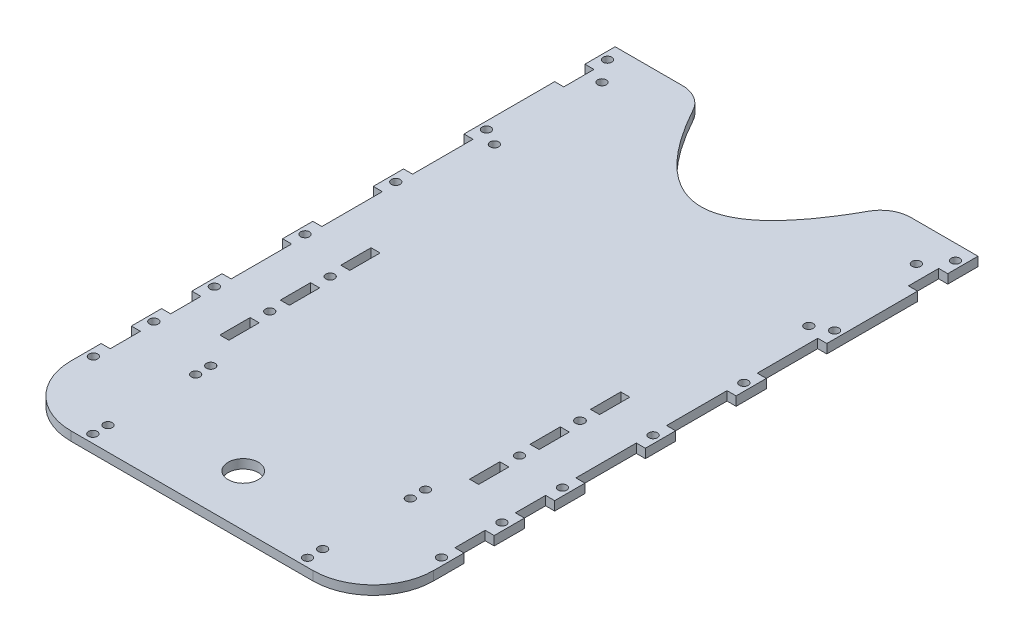
SolidWorks part; units mm, degrees
ref_plane "Front Plane" through (0, 0, 0) normal (0, 0, 1) x (1, 0, 0)
ref_plane "Top Plane" through (0, 0, 0) normal (0, 1, 0) x (1, 0, 0)
ref_plane "Right Plane" through (0, 0, 0) normal (1, 0, 0) x (0, 0, -1)
sketch "Sketch1" plane through (0, 0, 0) normal (0, 1, 0) x (1, 0, 0)
  line L1 (60, -100) -> (-60, -100)
  line L2 (60, -100) -> (60, 100)
  line L3 (60, 100) -> (-60, 100)
  line L4 (-60, -100) -> (-60, 100)
  line L5 (0, 100) -> (0, -100) construction
  line L6 (60, 0) -> (-60, 0) construction
  point P0 (0, 0)
  dimension "D1" = 200
  dimension "D2" = 120
extrude "Boss-Extrude1" add sketch "Sketch1" along normal blind 3
sketch "Sketch2" plane through (0, 3, 0) normal (0, 1, 0) x (1, 0, 0)
  line L0 (-60, -100) -> (60, -100) construction
  line L1 (-42.795, 2.0607) -> (-39.795, 2.0607)
  line L2 (-42.795, 2.0607) -> (-42.795, -47.9393)
  line L3 (-42.795, -47.9393) -> (-39.795, -47.9393)
  line L4 (-39.795, 2.0607) -> (-39.795, -47.9393)
  line L5 (39.795, 2.0607) -> (42.795, 2.0607)
  line L6 (39.795, 2.0607) -> (39.795, -47.9393)
  line L7 (39.795, -47.9393) -> (42.795, -47.9393)
  line L8 (42.795, 2.0607) -> (42.795, -47.9393)
  line L9 (-60, 100) -> (-60, -100) construction
  line L10 (0, 0) -> (0, -15.9466)
  line L11 (-24.2821, -64.5) -> (27.394, -64.5)
  line L12 (-24.2821, -91) -> (27.394, -91)
  line L13 (-42.795, -7.9393) -> (-39.795, -7.9393)
  line L14 (-42.795, -17.9393) -> (-39.795, -17.9393)
  line L15 (-42.795, -27.9393) -> (-39.795, -27.9393)
  line L16 (-42.795, -37.9393) -> (-39.795, -37.9393)
  line L17 (39.795, -7.9393) -> (42.795, -7.9393)
  line L18 (39.795, -17.9393) -> (42.795, -17.9393)
  line L19 (39.795, -27.9393) -> (42.795, -27.9393)
  line L20 (39.795, -37.9393) -> (42.795, -37.9393)
  line L21 (-60, 17.0607) -> (-60, 57.0607)
  line L22 (60, -100) -> (60, 100) construction
  circle A0 centre (0, -83) radius 5
  circle A1 centre (0, -83) radius 20
  circle A2 centre (35.5, -92.25) radius 1.44
  circle A3 centre (35.5, -97.25) radius 1.44
  circle A4 centre (-35.5, -92.25) radius 1.44
  circle A5 centre (-35.5, -97.25) radius 1.44
  circle A6 centre (-35.5, -63.25) radius 1.44
  circle A7 centre (-35.5, -58.25) radius 1.44
  circle A8 centre (35.5, -63.25) radius 1.44
  circle A9 centre (35.5, -58.25) radius 1.44
  circle A10 centre (-41.295, -32.9393) radius 1.44
  circle A11 centre (-41.295, -12.9393) radius 1.44
  circle A12 centre (41.295, -32.9393) radius 1.44
  circle A13 centre (41.295, -12.9393) radius 1.5
  circle A14 centre (-52, 52.0607) radius 1.44
  circle A15 centre (-52, 87.6207) radius 1.44
  circle A16 centre (52, 87.6207) radius 1.44
  circle A17 centre (52, 52.0607) radius 1.44
  point P74 (0, 0)
  dimension "D1" = 10
  dimension "D2" = 17
  dimension "D3" = 60
  dimension "D4" = 8
  dimension "D5" = 18.5
  dimension "D12" = 3
  dimension "D25" = 1.5
  dimension "D26" = 5
  dimension "D27" = 1.5
  dimension "D28" = 5
  dimension "D29" = 1.5
  dimension "D30" = 5
  dimension "D31" = 5
  dimension "D32" = 1.5
  dimension "D33" = 8
  dimension "D34" = 8
  dimension "D35" = 8
  dimension "D36" = 8
  dimension "D37" = 35.56
  dimension "D38" = 5
  dimension "D39" = 35.56
  dimension "D6" = 35.5
  dimension "D7" = 35.5
  dimension "D8" = 1.25
  dimension "D9" = 6.25
  dimension "D10" = 1.25
  dimension "D11" = 6.25
  dimension "D13" = 3
  dimension "D14" = 39.795
  dimension "D15" = 39.795
  dimension "D16" = 10
  dimension "D17" = 30
  dimension "D18" = 20
  dimension "D19" = 10
  dimension "D20" = 50
  dimension "D21" = 40
  dimension "D22" = 30
  dimension "D23" = 20
  dimension "D24" = 10
  dimension "D40" = 0
extrude "Cut-Extrude1" cut sketch "Sketch2" against normal through all contours A0 | A4 | A5 | A6 | A7 | A9 | A8 | A3 | A2 | L20 L6 L7 L8 | A12 | L6 L19 L8 L18 | L6 L17 L8 L5 | A13 | L16 L2 L3 L4 | A10 | L2 L15 L4 L14 | A11 | L2 L13 L4 L1 | A17 | A16 | A14 | A15
fillet "Fillet1" radius 20 2 edges at (60, 1.5, 100) (-60, 1.5, 100)
sketch "Sketch3" plane through (0, 3, 0) normal (0, 1, 0) x (1, 0, 0)
  line L0 (60, 100) -> (-60, 100) construction
  line L1 (-31.7405, 100) -> (31.7405, 100)
  parabola Q0 (-31.7405, 100) -> (31.7405, 100) focus (0, 76.334) apex (0, 68.371)
extrude "Cut-Extrude2" cut sketch "Sketch3" against normal through all
fillet "Fillet2" radius 10 2 edges at (31.7405, 1.5, -100) (-31.7405, 1.5, -100)
sketch "Sketch4" plane through (0, 3, 0) normal (0, 1, 0) x (1, 0, 0)
  line L0 (-60, 90) -> (-57, 90)
  line L1 (-60, 100) -> (-57, 100)
  line L2 (-60, 100) -> (-60, -80)
  line L3 (-60, -80) -> (-57, -80)
  line L4 (-57, 100) -> (-57, -80)
  line L5 (60, 100) -> (57, 100)
  line L6 (60, 100) -> (60, -80)
  line L7 (60, -80) -> (57, -80)
  line L8 (57, 100) -> (57, -80)
  line L9 (46.0167, 78.7307) -> (60, 78.7307)
  line L10 (46.0167, 78.7307) -> (46.0167, 60.9507)
  line L11 (46.0167, 60.9507) -> (60, 60.9507)
  line L12 (60, 78.7307) -> (60, 60.9507)
  line L13 (-46.0379, 78.7307) -> (-60, 78.7307)
  line L14 (-46.0379, 78.7307) -> (-46.0379, 60.9507)
  line L15 (-46.0379, 60.9507) -> (-60, 60.9507)
  line L16 (-60, 78.7307) -> (-60, 60.9507)
  line L17 (-60, 80) -> (-57, 80)
  line L18 (57, 90) -> (60, 90)
  line L19 (60, 80) -> (57, 80)
  line L20 (-60, -70) -> (-57, -70)
  line L21 (-60, -60) -> (-57, -60)
  line L22 (-60, -50) -> (-57, -50)
  line L23 (-60, -40) -> (-57, -40)
  line L24 (-60, -30) -> (-57, -30)
  line L25 (-60, -20) -> (-57, -20)
  line L26 (-60, -10) -> (-57, -10)
  line L27 (-60, 0) -> (-57, 0)
  line L28 (-60, 10) -> (-57, 10)
  line L29 (-60, 20) -> (-57, 20)
  line L30 (-60, 30) -> (-57, 30)
  line L31 (-60, 40) -> (-57, 40)
  line L32 (-60, 50) -> (-57, 50)
  line L33 (-60, 60) -> (-57, 60)
  circle A0 centre (-52, 87.6207) radius 1.44 construction
  circle A1 centre (-52, 52.0607) radius 1.44 construction
  circle A2 centre (52, 52.0607) radius 1.44 construction
  circle A3 centre (52, 87.6207) radius 1.44 construction
  circle A4 centre (-57.56, 95) radius 1.44
  circle A5 centre (-57.56, 55) radius 1.44
  circle A6 centre (-57.56, 25) radius 1.44
  circle A7 centre (-57.56, -5) radius 1.44
  circle A8 centre (-57.56, -35) radius 1.44
  circle A9 centre (-57.56, -75) radius 1.44
  circle A10 centre (-57.56, -55) radius 1.44
  point P54 (-58.5, -40)
  dimension "D3" = 8.89
  dimension "D5" = 8.89
  dimension "D6" = 8.89
  dimension "D26" = 2.44
  dimension "D28" = 0
  dimension "D32" = 5
  dimension "D38" = 5
  dimension "D1" = 3
  dimension "D2" = 3
  dimension "D4" = 8.89
  dimension "D7" = 10
  dimension "D8" = 10
  dimension "D9" = 10
  dimension "D10" = 10
  dimension "D11" = 10
  dimension "D12" = 10
  dimension "D13" = 10
  dimension "D14" = 10
  dimension "D15" = 10
  dimension "D16" = 10
  dimension "D17" = 10
  dimension "D18" = 10
  dimension "D19" = 10
  dimension "D20" = 10
  dimension "D21" = 10
  dimension "D22" = 10
  dimension "D23" = 10
  dimension "D24" = 10
  dimension "D25" = 20
  dimension "D27" = 0
  dimension "D29" = 0
  dimension "D30" = 0
  dimension "D31" = 0
  dimension "D33" = 5
  dimension "D34" = 5
  dimension "D35" = 5
  dimension "D36" = 5
  dimension "D37" = 5
extrude "Cut-Extrude3" cut sketch "Sketch4" against normal blind 3 contours L4 A9 | L21 L2 L20 L4 | L23 L2 L22 L4 | L25 L2 L24 L4 | L26 L2 L25 L4 | L28 L2 L27 L4 | L29 L2 L28 L4 | L32 L2 L31 L4 | L31 L2 L30 L4 | L2 L17 L4 L0 | A10 | A8 | A7 | A6 | A5 | A4
mirror "Mirror1" about plane through (0, 0, 0) normal (1, 0, 0) of "Cut-Extrude3"
